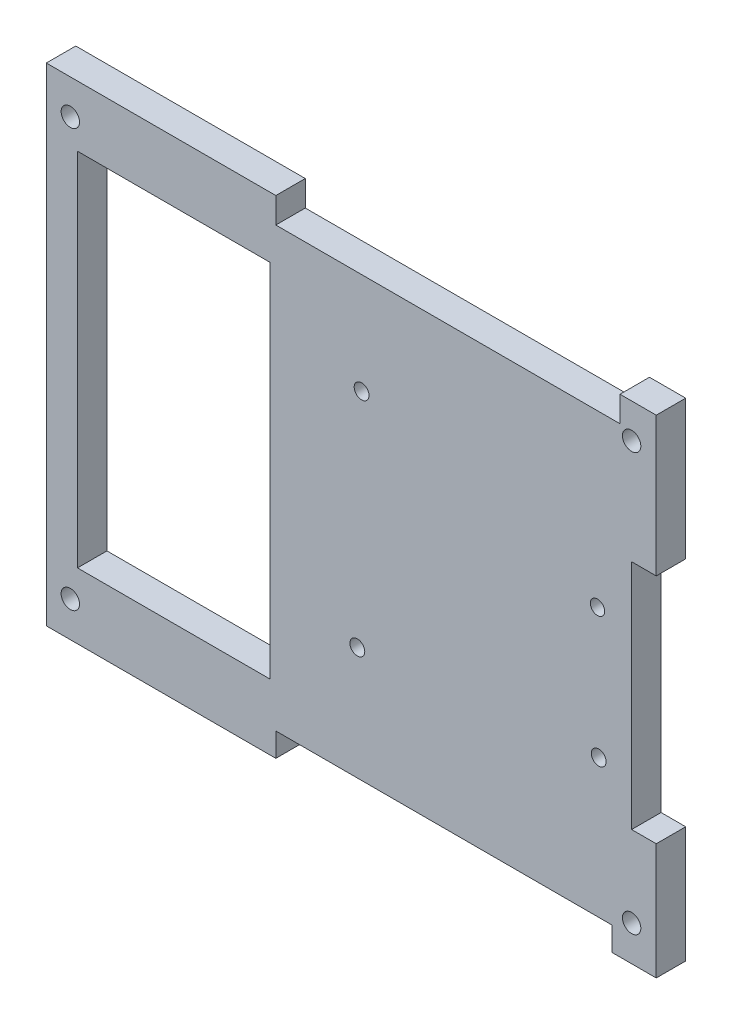
SolidWorks part; units mm, degrees
ref_plane "Front Plane" through (0, 0, 0) normal (0, 0, 1) x (1, 0, 0)
ref_plane "Top Plane" through (0, 0, 0) normal (0, 1, 0) x (1, 0, 0)
ref_plane "Right Plane" through (0, 0, 0) normal (1, 0, 0) x (0, 0, -1)
sketch "Sketch1" plane through (0, 0, 1332.0238) normal (0, 0, 1) x (1, 0, 0)
  line L1 (418.1784, 921.2704) -> (549.6694, 921.2704)
  line L2 (418.1784, 921.2704) -> (418.1784, 816.187)
  line L3 (418.1784, 816.187) -> (549.6694, 816.187)
  line L4 (549.6694, 921.2704) -> (549.6694, 816.187)
  circle A0 centre (423.3568, 913.8202) radius 1.9812
  circle A1 centre (544.3624, 913.8202) radius 1.9812
  circle A2 centre (544.3624, 823.8026) radius 1.9812
  circle A3 centre (423.3568, 823.8026) radius 1.9812
extrude "Base_Plate" add sketch "Sketch1" along normal blind 6.35
sketch "Sketch2" plane through (0, 0, 1338.3738) normal (0, 0, 1) x (1, 0, 0)
  circle A0 centre (486.149, 893.9583) radius 1.6
  circle A1 centre (537.0057, 879.0637) radius 1.5408
  circle A2 centre (537.2629, 851.1504) radius 1.6
  circle A3 centre (485.2314, 845.6903) radius 1.6
extrude "Arduino_Mounting_Holes" cut sketch "Sketch2" against normal blind 6.35
sketch "Sketch3" plane through (0, 0, 1338.3738) normal (0, 0, 1) x (1, 0, 0)
  line L1 (466.436, 908.1672) -> (424.9036, 908.1672)
  line L2 (466.436, 908.1672) -> (466.436, 830.3671)
  line L3 (466.436, 830.3671) -> (424.9036, 830.3671)
  line L4 (424.9036, 908.1672) -> (424.9036, 830.3671)
extrude "Cable_Opening" cut sketch "Sketch3" against normal blind 6.35
sketch "Sketch4" plane through (0, 0, 1338.3738) normal (0, 0, 1) x (1, 0, 0)
  line L0 (549.6694, 921.2704) -> (418.1784, 921.2704) construction
  line L1 (467.6586, 921.2704) -> (541.8597, 921.2704)
  line L2 (467.6586, 921.2704) -> (467.6586, 915.761)
  line L3 (467.6586, 915.761) -> (541.8597, 915.761)
  line L4 (541.8597, 921.2704) -> (541.8597, 915.761)
  line L5 (418.1784, 816.187) -> (549.6694, 816.187) construction
  line L6 (540.1596, 816.187) -> (467.6581, 816.187)
  line L7 (540.1596, 816.187) -> (540.1596, 821.3037)
  line L8 (540.1596, 821.3037) -> (467.6581, 821.3037)
  line L9 (467.6581, 816.187) -> (467.6581, 821.3037)
  line L10 (443.4244, 821.3037) -> (514.7244, 821.3037) construction
  line L11 (549.6694, 816.187) -> (549.6694, 921.2704) construction
  line L12 (549.6694, 891.2549) -> (544.3624, 891.2549)
  line L13 (549.6694, 891.2549) -> (549.6694, 841.2516)
  line L14 (549.6694, 841.2516) -> (544.3624, 841.2516)
  line L15 (544.3624, 891.2549) -> (544.3624, 841.2516)
extrude "Cut-Extrude3" cut sketch "Sketch4" against normal blind 6.35
